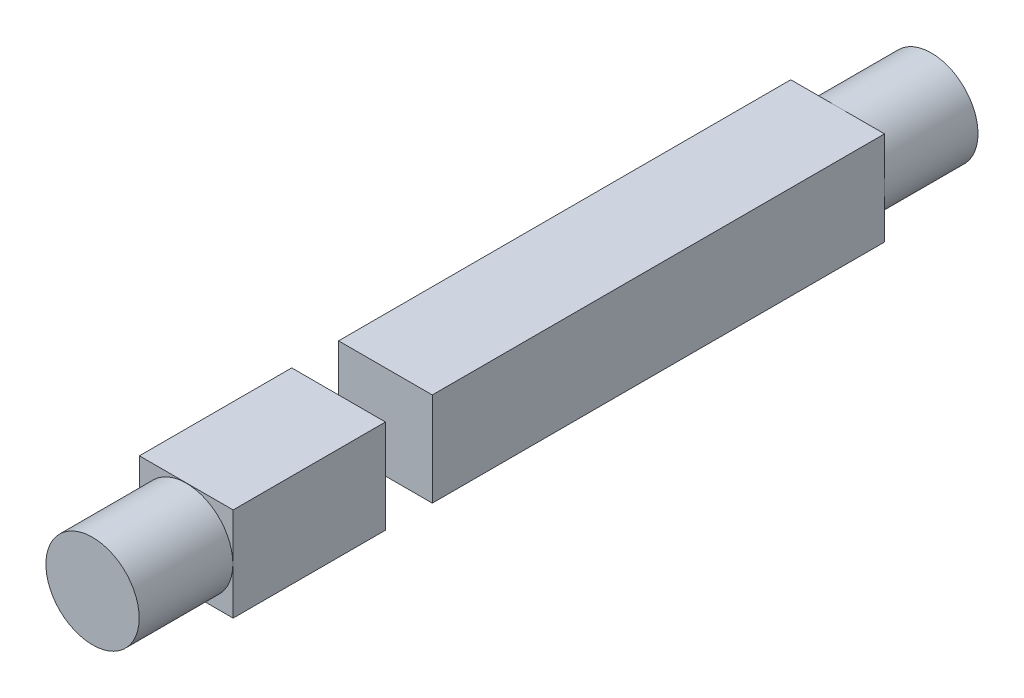
SolidWorks part; units mm, degrees
ref_plane "Front Plane" through (0, 0, 0) normal (0, 0, 1) x (1, 0, 0)
ref_plane "Top Plane" through (0, 0, 0) normal (0, 1, 0) x (1, 0, 0)
ref_plane "Right Plane" through (0, 0, 0) normal (1, 0, 0) x (0, 0, -1)
sketch "Sketch1" plane through (0, 0, 0) normal (0, 0, 1) x (1, 0, 0)
  line L1 (2, -2) -> (-2, -2)
  line L2 (2, -2) -> (2, 2)
  line L3 (2, 2) -> (-2, 2)
  line L4 (-2, -2) -> (-2, 2)
  line L5 (2, -2) -> (-2, 2) construction
  line L6 (2, 2) -> (-2, -2) construction
  dimension "D2" = 4
extrude "Boss-Extrude1" add sketch "Sketch1" along normal mid plane 27.8
sketch "Sketch2" plane through (0, 0, 13.9) normal (0, 0, 1) x (1, 0, 0)
  circle A0 centre (0, 0) radius 1.99
  dimension "D1" = 3.98
extrude "Boss-Extrude2" add sketch "Sketch2" along normal blind 4
mirror "Mirror2" about plane through (0, 0, 0) normal (0, 0, 1) of "Boss-Extrude2"
sketch "Sketch3" plane through (0, 2, 0) normal (0, 1, 0) x (1, 0, 0)
  line L0 (-2, -13.9) -> (-2, 13.9) construction
  line L1 (-2, -7.4) -> (2, -7.4)
  line L2 (-2, -7.4) -> (-2, -5.4)
  line L3 (-2, -5.4) -> (2, -5.4)
  line L4 (2, -7.4) -> (2, -5.4)
  line L5 (2, -13.9) -> (2, 13.9) construction
  line L7 (2, -13.9) -> (-2, -13.9) construction
  dimension "D1" = 2
  dimension "D2" = 6.5
extrude "Cut-Extrude1" cut sketch "Sketch3" against normal up to next
